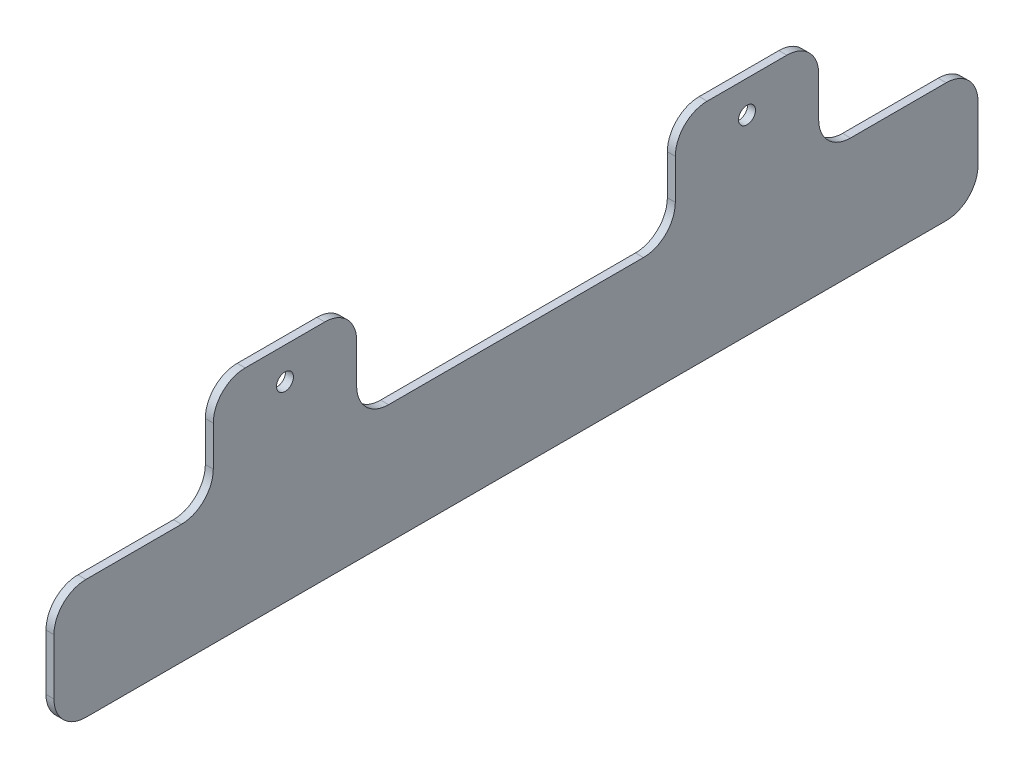
SolidWorks part; units mm, degrees
material "PC High Viscosity"
ref_plane "Front Plane" through (0, 0, 0) normal (0, 0, 1) x (1, 0, 0)
ref_plane "Top Plane" through (0, 0, 0) normal (0, 1, 0) x (1, 0, 0)
ref_plane "Right Plane" through (0, 0, 0) normal (1, 0, 0) x (0, 0, -1)
sketch "Sketch1" plane through (0, 0, 0) normal (1, 0, 0) x (0, 0, -1)
  line L0 (12.7, 0) -> (355.6, 0)
  line L1 (368.3, 12.7) -> (368.3, 34.925)
  line L2 (355.6, 47.625) -> (317.5, 47.625)
  line L3 (304.8, 60.325) -> (304.8, 76.2)
  line L4 (292.1, 88.9) -> (260.35, 88.9)
  line L5 (63.5, 76.2) -> (63.5, 60.325)
  line L6 (50.8, 47.625) -> (12.7, 47.625)
  line L7 (0, 34.925) -> (0, 12.7)
  line L9 (120.65, 76.2) -> (120.65, 60.325)
  line L10 (247.65, 76.2) -> (247.65, 60.325)
  line L11 (133.35, 47.625) -> (234.95, 47.625)
  line L12 (107.95, 88.9) -> (76.2, 88.9)
  arc A0 (12.7, 0) -> (0, 12.7) centre (12.7, 12.7) cw
  arc A1 (355.6, 0) -> (368.3, 12.7) centre (355.6, 12.7) ccw
  arc A2 (368.3, 34.925) -> (355.6, 47.625) centre (355.6, 34.925) ccw
  arc A3 (317.5, 47.625) -> (304.8, 60.325) centre (317.5, 60.325) cw
  arc A4 (304.8, 76.2) -> (292.1, 88.9) centre (292.1, 76.2) ccw
  arc A5 (76.2, 88.9) -> (63.5, 76.2) centre (76.2, 76.2) ccw
  arc A6 (63.5, 60.325) -> (50.8, 47.625) centre (50.8, 60.325) cw
  arc A7 (12.7, 47.625) -> (0, 34.925) centre (12.7, 34.925) ccw
  circle A8 centre (92.075, 76.2) radius 3.3734
  circle A9 centre (276.225, 76.2) radius 3.3734
  arc A10 (247.65, 60.325) -> (234.95, 47.625) centre (234.95, 60.325) cw
  arc A11 (260.35, 88.9) -> (247.65, 76.2) centre (260.35, 76.2) ccw
  arc A12 (120.65, 60.325) -> (133.35, 47.625) centre (133.35, 60.325) ccw
  arc A13 (120.65, 76.2) -> (107.95, 88.9) centre (107.95, 76.2) ccw
  point P11 (0, 0)
  point P16 (368.3, 47.625)
  point P19 (304.8, 47.625)
  point P22 (304.8, 88.9)
  point P25 (63.5, 88.9)
  point P28 (63.5, 47.625)
  point P31 (0, 47.625)
  point P40 (247.65, 47.625)
  point P47 (120.65, 47.625)
  point P50 (120.65, 88.9)
  dimension "D7" = 12.7
  dimension "D9" = 6.7469
  dimension "D16" = 12.7
  dimension "D1" = 241.3
  dimension "D2" = 41.275
  dimension "D3" = 41.275
  dimension "D4" = 47.625
  dimension "D5" = 63.5
  dimension "D6" = 63.5
  dimension "D8" = 184.15
  dimension "D10" = 28.575
  dimension "D11" = 12.7
  dimension "D12" = 41.275
  dimension "D13" = 57.15
  dimension "D14" = 57.15
  dimension "D15" = 127
extrude "Boss-Extrude1" add sketch "Sketch1" along normal blind 3.175
